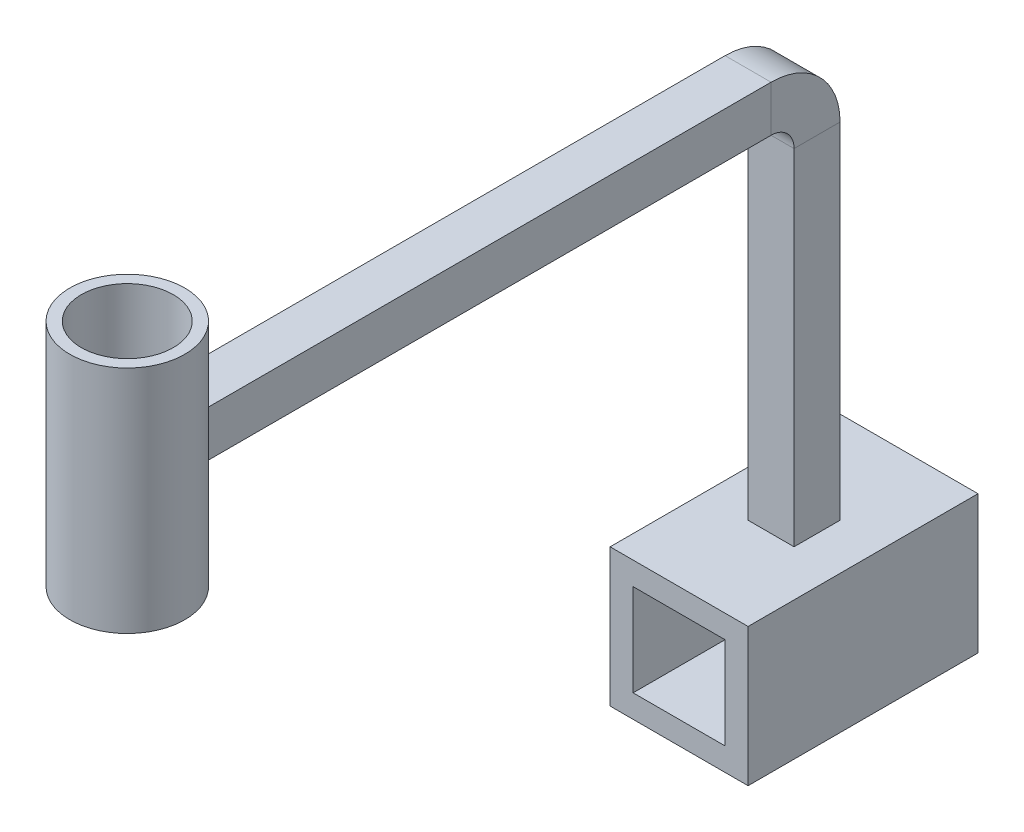
SolidWorks part; units mm, degrees
material "Acier non allié"
ref_plane "Plan de face" through (0, 0, 0) normal (0, 0, 1) x (1, 0, 0)
ref_plane "Plan de dessus" through (0, 0, 0) normal (0, 1, 0) x (1, 0, 0)
ref_plane "Plan de droite" through (0, 0, 0) normal (1, 0, 0) x (0, 0, -1)
sketch "Esquisse1" plane through (0, 0, 0) normal (0, 0, 1) x (1, 0, 0)
  line L1 (-2, 2) -> (2, 2)
  line L2 (-2, 2) -> (-2, -2)
  line L3 (-2, -2) -> (2, -2)
  line L4 (2, 2) -> (2, -2)
  line L5 (-2, 2) -> (2, -2) construction
  line L6 (-2, -2) -> (2, 2) construction
  line L7 (-3, 3) -> (3, 3)
  line L8 (-3, 3) -> (-3, -3)
  line L9 (-3, -3) -> (3, -3)
  line L10 (3, 3) -> (3, -3)
  line L11 (-3, 3) -> (3, -3) construction
  line L12 (-3, -3) -> (3, 3) construction
  point P0 (0, 0)
  point P6 (0, 0)
  dimension "D1" = 4
  dimension "D2" = 4
  dimension "D3" = 6
  dimension "D4" = 6
extrude "Boss.-Extru.1" add sketch "Esquisse1" along normal blind 10
sketch "Esquisse2" plane through (0, 3, 0) normal (0, 1, 0) x (1, 0, 0)
  line L0 (0, 0) -> (0, -11.0721) construction
  line L1 (1, -6) -> (-1, -6)
  line L2 (1, -6) -> (1, -4)
  line L3 (1, -4) -> (-1, -4)
  line L4 (-1, -6) -> (-1, -4)
  line L5 (1, -6) -> (-1, -4) construction
  line L6 (1, -4) -> (-1, -6) construction
  line L7 (3, 0) -> (-3, 0) construction
  line L10 (-7.7593, -5) -> (11.5662, -5) construction
  line L11 (3, -10) -> (-3, -10) construction
  point P0 (0, -5)
  dimension "D3" = 2
  dimension "D4" = 2
sketch "Esquisse3" plane through (0, 0, 0) normal (1, 0, 0) x (0, 0, -1)
  line L0 (-5, 3) -> (-5, 18)
  line L1 (-4, 3) -> (-6, 3) construction
  line L2 (-7, 20) -> (-32, 20)
  arc A0 (-5, 18) -> (-7, 20) centre (-7, 18) ccw
  dimension "D1" = 2
  dimension "D2" = 15
  dimension "D3" = 25
sweep "Balayage1" add profiles "Esquisse2" path "Esquisse3"
sketch "Esquisse4" plane through (0, 19, 0) normal (0, -1, 0) x (1, 0, 0)
  line L0 (0, 0) -> (0, 26.1552) construction
  line L1 (-1, 32) -> (1, 32) construction
  circle A0 centre (0, 34) radius 2.5
  circle A1 centre (0, 34) radius 2
  dimension "D1" = 5
  dimension "D2" = 4
  dimension "D3" = 2
extrude "Boss.-Extru.2" add sketch "Esquisse4" along normal blind 4 and the other way blind 6 contours A1 | A0
